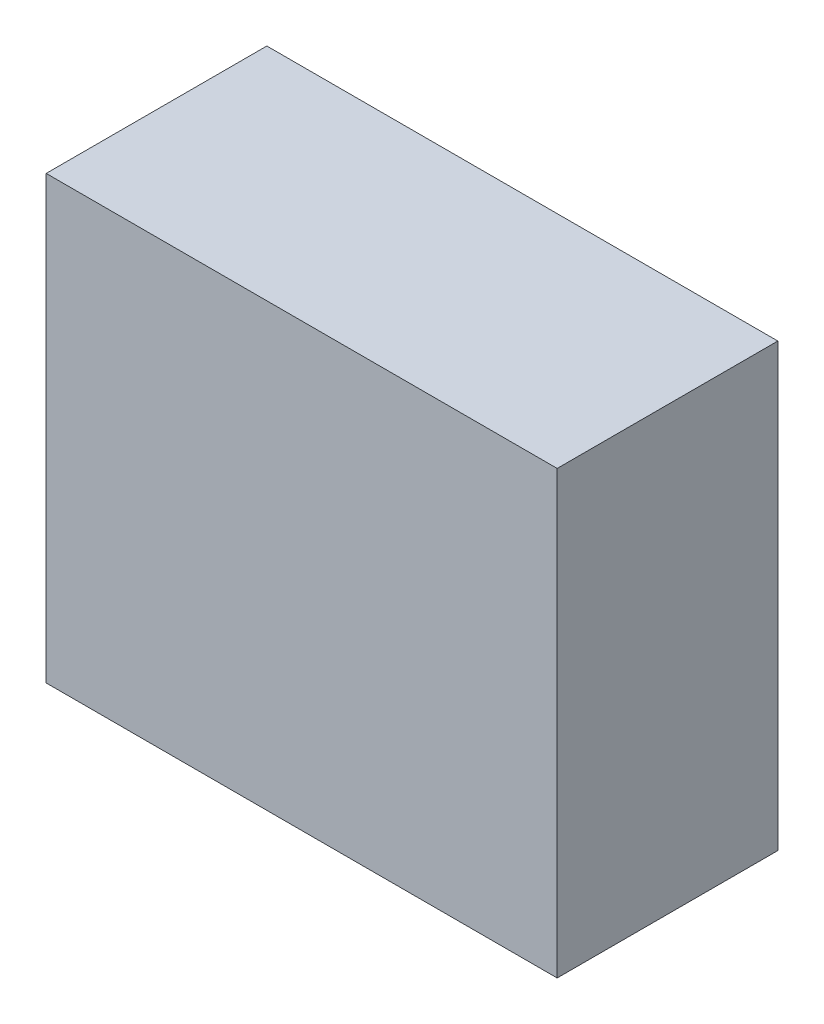
SolidWorks part; units mm, degrees
ref_plane "Front Plane" through (0, 0, 0) normal (0, 0, 1) x (1, 0, 0)
ref_plane "Top Plane" through (0, 0, 0) normal (0, 1, 0) x (1, 0, 0)
ref_plane "Right Plane" through (0, 0, 0) normal (1, 0, 0) x (0, 0, -1)
ref_plane "PL_Box_0_base" through (0, 0, 100) normal (0, 0, 1) x (1, 0, 0)
sketch "SK_Box_0" plane through (0, 0, 100) normal (0, 0, 1) x (1, 0, 0)
  line L0 (-46, -80) -> (-2, -80)
  line L1 (-2, -80) -> (-2, -42)
  line L2 (-2, -42) -> (-46, -42)
  line L3 (-46, -42) -> (-46, -80)
  dimension "P1" = 46
  dimension "P2" = 80
  dimension "P3" = 2
  dimension "P4" = 80
  dimension "P5" = 2
  dimension "P6" = 42
  dimension "P7" = 46
  dimension "P8" = 42
extrude "Box_0" add sketch "SK_Box_0" along normal blind 19
